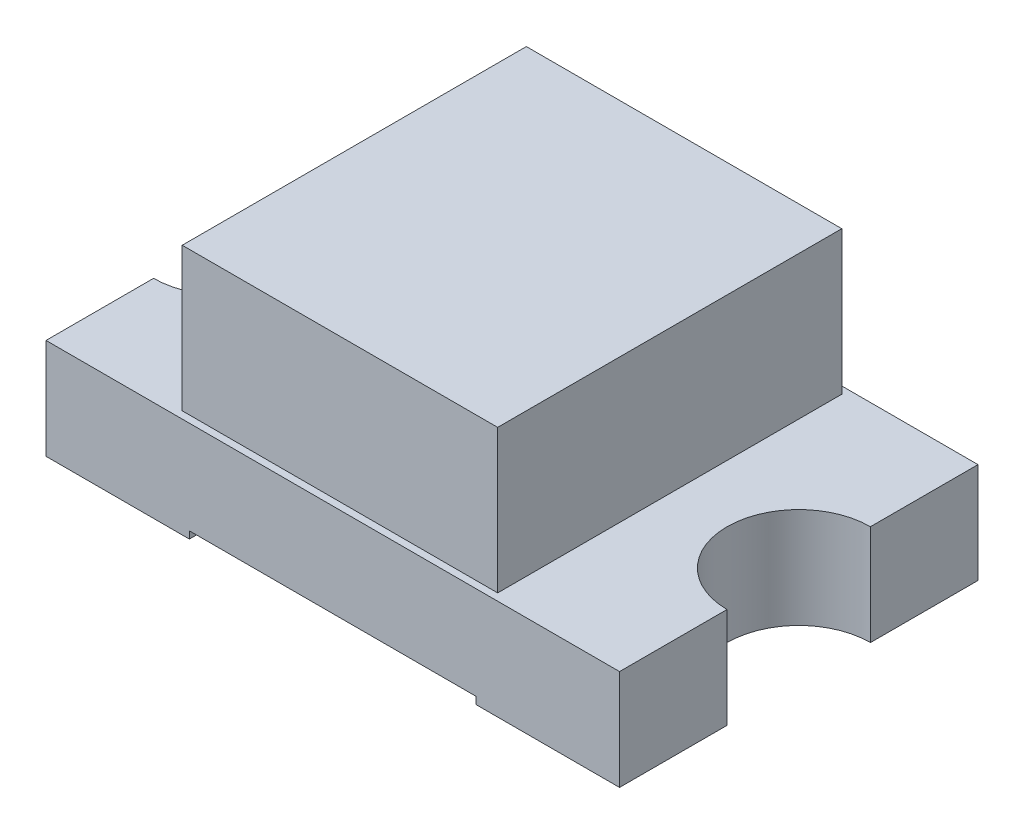
SolidWorks part; units mm, degrees
ref_plane "Front Plane" through (0, 0, 0) normal (0, 0, 1) x (1, 0, 0)
ref_plane "Top Plane" through (0, 0, 0) normal (0, 1, 0) x (1, 0, 0)
ref_plane "Right Plane" through (0, 0, 0) normal (1, 0, 0) x (0, 0, -1)
sketch "Sketch1" plane through (0, 0, 0) normal (0, 1, 0) x (1, 0, 0)
  line L1 (-2.032, 1.27) -> (0, 1.27)
  line L2 (-2.032, 1.27) -> (-2.032, 0)
  line L3 (-2.032, 0) -> (0, 0)
  line L4 (0, 1.27) -> (0, 0)
  circle A0 centre (-2.032, 0.635) radius 0.254
  circle A1 centre (0, 0.635) radius 0.254
  dimension "D3" = 0.508
  dimension "D4" = 0.508
  dimension "D1" = 1.27
  dimension "D2" = 2.032
extrude "Boss-Extrude1" add sketch "Sketch1" along normal blind 0.3302 contours A1 L4 L1 L2 A0 L3
sketch "Sketch2" plane through (0, 0, 0) normal (0, -1, 0) x (1, 0, 0)
  line L0 (-1.524, -1.27) -> (-1.524, 0)
  line L1 (-0.508, 0) -> (-0.508, -1.27)
  line L3 (-0.508, -0.4191) -> (-0.9398, -0.4191)
  line L4 (-0.508, -0.4191) -> (-0.508, -0.8509)
  line L5 (-0.508, -0.8509) -> (-0.9398, -0.8509)
  line L6 (0, -0.381) -> (0, 0)
  line L7 (0, 0) -> (-2.032, 0)
  line L8 (-2.032, 0) -> (-2.032, -0.381)
  line L9 (-2.032, -0.889) -> (-2.032, -1.27)
  line L10 (-2.032, -1.27) -> (0, -1.27)
  line L11 (0, -1.27) -> (0, -0.889)
  line L12 (0, -0.381) -> (0, 0)
  line L13 (0, 0) -> (-2.032, 0)
  line L14 (-2.032, 0) -> (-2.032, -0.381)
  line L15 (-2.032, -0.889) -> (-2.032, -1.27)
  line L16 (-2.032, -1.27) -> (0, -1.27)
  line L17 (0, -1.27) -> (0, -0.889)
  line L18 (-0.9398, -0.4191) -> (-0.9398, -0.8509)
  arc A2 (0, -0.381) -> (0, -0.889) centre (0, -0.635) ccw
  arc A3 (-2.032, -0.889) -> (-2.032, -0.381) centre (-2.032, -0.635) ccw
  arc A4 (0, -0.381) -> (0, -0.889) centre (0, -0.635) ccw
  arc A5 (-2.032, -0.889) -> (-2.032, -0.381) centre (-2.032, -0.635) ccw
  point P18 (-0.9398, -0.635)
  arc M14 (0, -0.889) -> (0, -0.381) centre (0, -0.635) cw
  line M15 (0, -0.381) -> (0, 0)
  line M16 (0, 0) -> (-2.032, 0)
  line M17 (-2.032, 0) -> (-2.032, -0.381)
  arc M18 (-2.032, -0.381) -> (-2.032, -0.889) centre (-2.032, -0.635) cw
  line M19 (-2.032, -0.889) -> (-2.032, -1.27)
  line M20 (-2.032, -1.27) -> (0, -1.27)
  line M21 (0, -1.27) -> (0, -0.889)
  dimension "D2" = 0.508
  dimension "D3" = 0.508
  dimension "D4" = 0.4318
  dimension "D5" = 0.4318
  dimension "D6" = 0.635
  dimension "D1" = 0
extrude "Boss-Extrude2" add sketch "Sketch2" along normal blind 0.0254 contours L0 M20 M16 M17 M18 M19 | L3 L18 L5 L1 | L1 M16 M20 M21 M14 M15
sketch "Sketch3" plane through (0, 0.3302, 0) normal (0, 1, 0) x (1, 0, 0)
  line L0 (-2.032, 1.27) -> (0, 1.27) construction
  line L2 (-1.5748, 1.27) -> (-1.5748, 0)
  line L3 (-1.5748, 1.2446) -> (-0.4572, 1.2446)
  line L4 (-0.4572, 1.27) -> (-0.4572, 0)
  line L5 (-2.032, 0) -> (0, 0) construction
  line L6 (-2.032, 1.27) -> (-2.032, 0.889) construction
  line L8 (-1.5748, 0.0254) -> (-0.4572, 0.0254)
  dimension "D1" = 0.4572
  dimension "D2" = 1.1176
  dimension "D3" = 0.0254
  dimension "D4" = 0.0254
extrude "Boss-Extrude4" add sketch "Sketch3" along normal blind 0.508 contours L2 L8 L4 L3
sketch "Sketch4" plane through (0, 0.3302, 0) normal (0, 1, 0) x (1, 0, 0)
  line L1 (-0.9652, 0.8001) -> (-0.635, 0.8001)
  line L2 (-0.9652, 0.8001) -> (-0.9652, 0.4699)
  line L3 (-0.9652, 0.4699) -> (-0.635, 0.4699)
  line L4 (-0.635, 0.8001) -> (-0.635, 0.4699)
  line L5 (0, 1.27) -> (0, 0.889) construction
  dimension "D1" = 0.3302
  dimension "D2" = 0.3302
  dimension "D4" = 0.635
extrude "Boss-Extrude3" add sketch "Sketch4" along normal blind 0.3302
